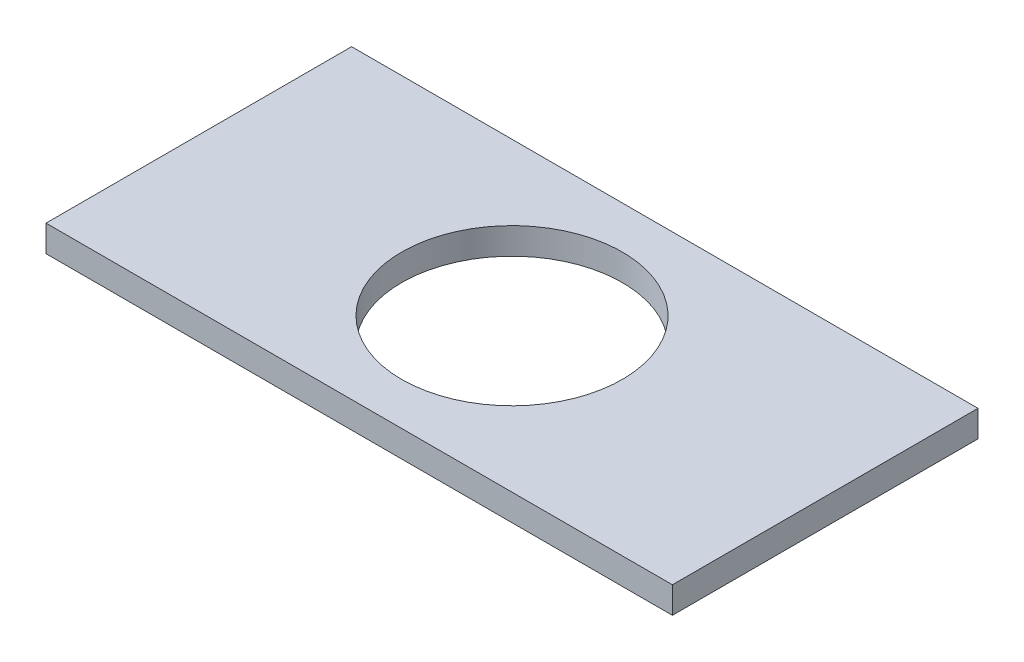
SolidWorks part; units mm, degrees
ref_plane "Front Plane" through (0, 0, 0) normal (0, 0, 1) x (1, 0, 0)
ref_plane "Top Plane" through (0, 0, 0) normal (0, 1, 0) x (1, 0, 0)
ref_plane "Right Plane" through (0, 0, 0) normal (1, 0, 0) x (0, 0, -1)
sketch "Sketch1" plane through (0, 0, 0) normal (0, 1, 0) x (1, 0, 0)
  line L1 (-118.2733, -57.7053) -> (118.2733, -57.7053)
  line L2 (-118.2733, -57.7053) -> (-118.2733, 57.7053)
  line L3 (-118.2733, 57.7053) -> (118.2733, 57.7053)
  line L4 (118.2733, -57.7053) -> (118.2733, 57.7053)
  line L5 (-118.2733, -57.7053) -> (118.2733, 57.7053) construction
  line L6 (-118.2733, 57.7053) -> (118.2733, -57.7053) construction
  circle A0 centre (0, 0) radius 41.6727
  point P0 (0, 0)
extrude "Boss-Extrude1" add sketch "Sketch1" along normal blind 10
